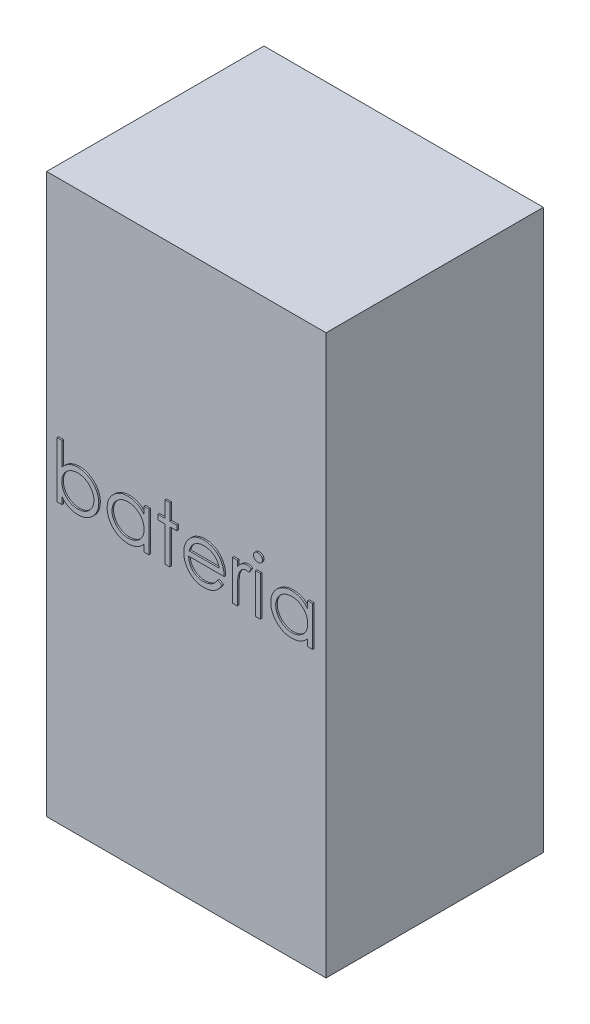
SolidWorks part; units mm, degrees
ref_plane "Front Plane" through (0, 0, 0) normal (0, 0, 1) x (1, 0, 0)
ref_plane "Top Plane" through (0, 0, 0) normal (0, 1, 0) x (1, 0, 0)
ref_plane "Right Plane" through (0, 0, 0) normal (1, 0, 0) x (0, 0, -1)
sketch "Sketch1" plane through (0, 0, 0) normal (0, 0, 1) x (1, 0, 0)
  line L1 (0, 0) -> (18, 0)
  line L2 (0, 0) -> (0, -36)
  line L3 (0, -36) -> (18, -36)
  line L4 (18, 0) -> (18, -36)
  dimension "D1" = 36
  dimension "D2" = 18
extrude "Boss-Extrude1" add sketch "Sketch1" along normal blind 14
sketch "Sketch2" plane through (0, 0, 14) normal (0, 0, 1) x (1, 0, 0)
  line L0 (0, -18) -> (18, -18) construction
  line L1 (0, 0) -> (0, -36) construction
  line L2 (18, -36) -> (18, 0) construction
  text T0 "bateria\r\n"
extrude "Boss-Extrude2" add sketch "Sketch2" along normal blind 0.1
